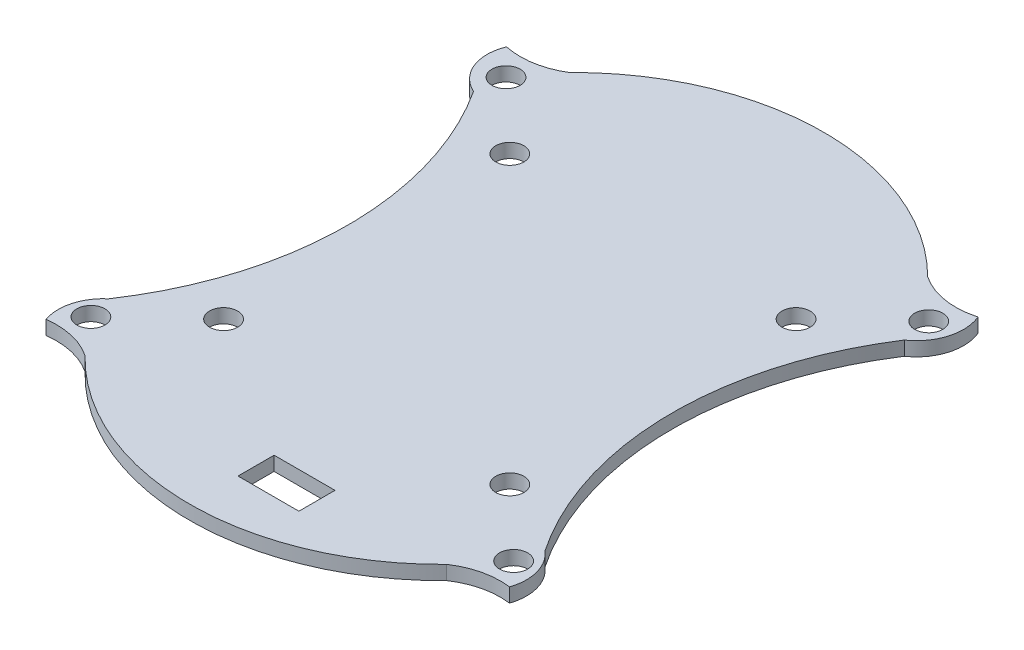
SolidWorks part; units mm, degrees
ref_plane "Front Plane" through (0, 0, 0) normal (0, 0, 1) x (1, 0, 0)
ref_plane "Top Plane" through (0, 0, 0) normal (0, 1, 0) x (1, 0, 0)
ref_plane "Right Plane" through (0, 0, 0) normal (1, 0, 0) x (0, 0, -1)
sketch "Sketch2" plane through (0, 0, 0) normal (0, 1, 0) x (1, 0, 0)
  line L1 (-15.25, 15.25) -> (15.25, 15.25)
  line L2 (-15.25, 15.25) -> (-15.25, -15.25)
  line L3 (-15.25, -15.25) -> (15.25, -15.25)
  line L4 (15.25, 15.25) -> (15.25, -15.25)
  line L5 (-15.25, 15.25) -> (15.25, -15.25) construction
  line L6 (-15.25, -15.25) -> (15.25, 15.25) construction
  line L8 (-78.5, 78.4165) -> (-78.5, -78.5835)
  line L13 (-78.5, 78.4165) -> (78.5, 78.4165)
  line L19 (-78.5, -78.5835) -> (78.5, -78.5835)
  line L24 (78.5, 78.4165) -> (78.5, -78.5835)
  line L27 (0, -25.1156) -> (6.4886, -25.1156)
  line L30 (0, -25.1156) -> (0, -28.9622)
  line L33 (0, -28.9622) -> (6.4886, -28.9622)
  line L34 (6.4886, -25.1156) -> (6.4886, -28.9622)
  line L59 (0, 78.5) -> (0, 103.571)
  line L125 (0, -15.25) -> (0, -6.7613)
  line L126 (0, 0) -> (5.3428, 0)
  circle A0 centre (-15.25, 15.25) radius 1.5
  circle A1 centre (15.25, 15.25) radius 1.5
  circle A2 centre (-15.25, -15.25) radius 1.5
  circle A3 centre (15.25, -15.25) radius 1.5
  circle A4 centre (-78.5, 78.4165) radius 64.77
  circle A7 centre (-78.5, -78.5835) radius 64.77
  arc A100 (23.248, -19.5002) -> (24.6954, -24.726) centre (20.1332, -23.1763) cw
  arc A102 (-23.248, -19.5002) -> (-24.6954, -24.726) centre (-20.1332, -23.1763) ccw
  arc A106 (-24.6954, -24.726) -> (-19.2641, -25.9972) centre (-23.6559, -32.5227) cw
  arc A107 (24.6954, -24.726) -> (19.2641, -25.9972) centre (23.6559, -32.5227) ccw
  arc A108 (-19.2641, -25.9972) -> (19.2641, -25.9972) centre (0, -7.2687) ccw
  circle A112 centre (78.5, -78.5835) radius 64.77
  circle A113 centre (78.5, 78.4165) radius 64.77
  arc A116 (22.9454, 19.0826) -> (24.7502, 25.1359) centre (20.1332, 23.2168) ccw
  arc A117 (24.7502, 25.1359) -> (18.3599, 26.1637) centre (22.6669, 32.5632) cw
  arc A118 (-22.9454, 19.0826) -> (-25.2944, 24.9511) centre (-21.1221, 23.2168) cw
  arc A119 (-25.2944, 24.9511) -> (-19.5823, 25.9273) centre (-23.6559, 32.5632) ccw
  arc A120 (-19.5823, 25.9273) -> (18.3599, 26.1637) centre (-0.4945, 7.3093) cw
  arc A121 (-22.9454, 19.0826) -> (-23.248, -19.5002) centre (-52.2988, 0.0203) cw
  arc A127 (22.9454, 19.0826) -> (23.248, -19.5002) centre (52.2988, 0.0203) ccw
  circle A148 centre (-22.5199, 22.1165) radius 1.5
  circle A149 centre (22.5199, 22.1165) radius 1.5
  circle A150 centre (22.5199, -22.1165) radius 1.5
  circle A151 centre (-22.5199, -22.1165) radius 1.5
  point P0 (0, 0)
  point P10 (0, 0)
  point P293 (-22.5, -22.275)
  dimension "D3" = 157
  dimension "D5" = 10
  dimension "D4" = 10
  dimension "D1" = 30.5
  dimension "D2" = 30.5
extrude "Boss-Extrude2" add sketch "Sketch2" along normal blind 1.5
sketch "Sketch3" plane through (0, 1.5, 0) normal (0, 1, 0) x (1, 0, 0)
sketch "Sketch4" plane through (0, 1.5, 0) normal (0, 1, 0) x (1, 0, 0)
sketch "Sketch5" plane through (0, 1.5, 0) normal (0, 1, 0) x (1, 0, 0)
